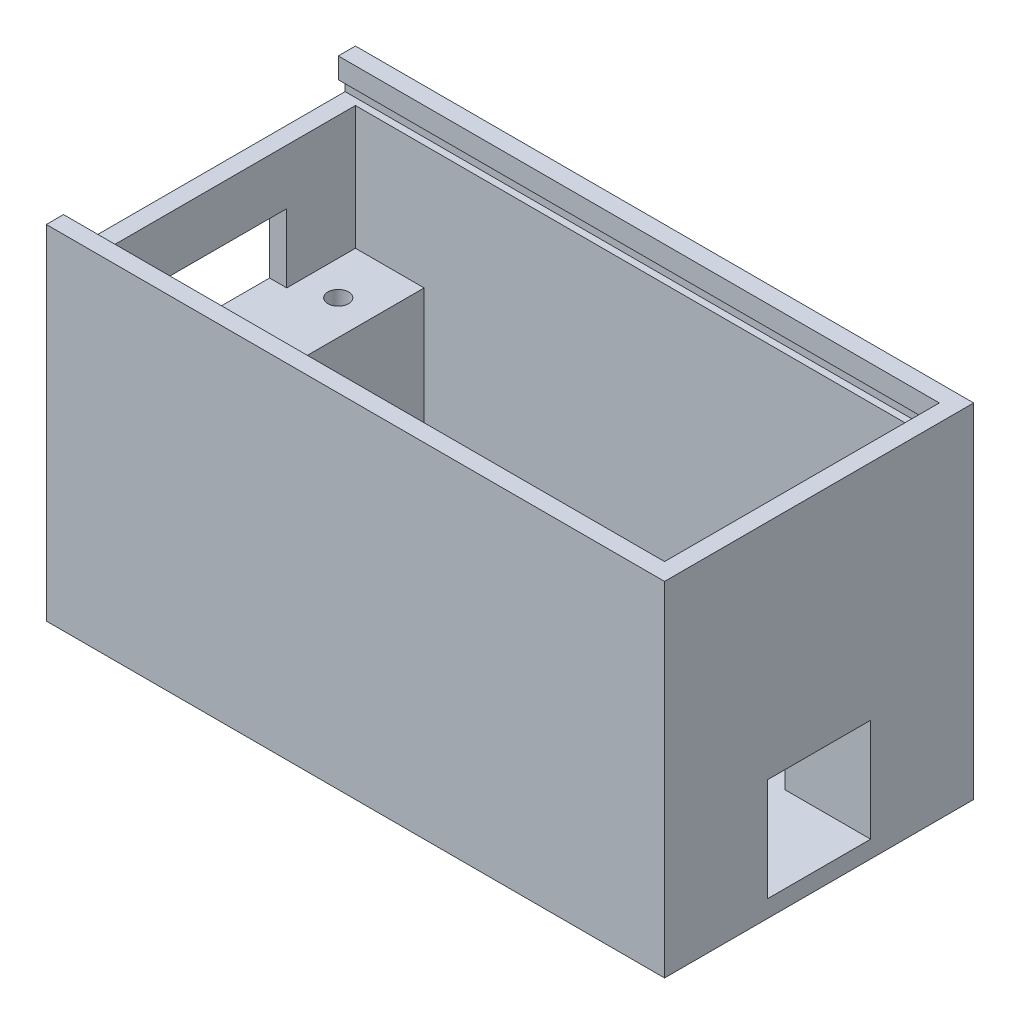
SolidWorks part; units mm, degrees
ref_plane "Front Plane" through (0, 0, 0) normal (0, 0, 1) x (1, 0, 0)
ref_plane "Top Plane" through (0, 0, 0) normal (0, 1, 0) x (1, 0, 0)
ref_plane "Right Plane" through (0, 0, 0) normal (1, 0, 0) x (0, 0, -1)
sketch "Sketch1" plane through (0, 0, 0) normal (0, 1, 0) x (1, 0, 0)
  line L1 (-40.1376, 25.9551) -> (49.8624, 25.9551)
  line L2 (-40.1376, 25.9551) -> (-40.1376, -19.0449)
  line L3 (-40.1376, -19.0449) -> (49.8624, -19.0449)
  line L4 (49.8624, 25.9551) -> (49.8624, -19.0449)
extrude "Boss-Extrude1" add sketch "Sketch1" along normal blind 50
shell "Shell1" thickness 2.5
sketch "Sketch2" plane through (-37.6376, 0, 0) normal (1, 0, 0) x (0, 0, -1)
  line L0 (-16.5449, 50) -> (-16.5449, 2.5) construction
  line L1 (23.4551, 2.5) -> (-16.5449, 2.5)
  line L2 (23.4551, 2.5) -> (23.4551, 27)
  line L3 (23.4551, 27) -> (-16.5449, 27)
  line L4 (-16.5449, 2.5) -> (-16.5449, 27)
extrude "Boss-Extrude2" add sketch "Sketch2" along normal blind 10
sketch "Sketch3" plane through (47.3624, 0, 0) normal (-1, 0, 0) x (0, 0, 1)
  line L0 (16.5449, 50) -> (16.5449, 2.5) construction
  line L5 (-23.4551, 2.5) -> (16.5449, 2.5)
  line L6 (-23.4551, 2.5) -> (-23.4551, 22)
  line L7 (-23.4551, 22) -> (16.5449, 22)
  line L8 (16.5449, 2.5) -> (16.5449, 22)
extrude "Boss-Extrude3" add sketch "Sketch3" along normal blind 10
sketch "Sketch9" plane through (-37.6376, 0, 0) normal (1, 0, 0) x (0, 0, -1)
  line L1 (23.4551, 27) -> (-16.5449, 27) construction
  line L2 (13.4551, 37) -> (-6.5449, 37)
  line L3 (13.4551, 37) -> (13.4551, 27)
  line L4 (13.4551, 27) -> (-6.5449, 27)
  line L5 (-6.5449, 37) -> (-6.5449, 27)
  line L6 (13.4551, 37) -> (-6.5449, 27) construction
  line L7 (13.4551, 27) -> (-6.5449, 37) construction
  point P3 (3.4551, 34.5)
  point P4 (3.4551, 32)
extrude "Cut-Extrude3" cut sketch "Sketch9" against normal blind 2.5
sketch "Sketch13" plane through (-37.6376, 0, 0) normal (1, 0, 0) x (0, 0, -1)
  line L0 (-16.5449, 50) -> (-16.5449, 27) construction
  line L1 (23.4551, 50) -> (-16.5449, 50)
  line L2 (23.4551, 50) -> (23.4551, 45)
  line L3 (23.4551, 45) -> (-16.5449, 45)
  line L4 (-16.5449, 50) -> (-16.5449, 45)
extrude "Cut-Extrude6" cut sketch "Sketch13" against normal blind 2.5
sketch "Sketch14" plane through (0, 0, -23.4551) normal (0, 0, 1) x (1, 0, 0)
  line L0 (47.3624, 50) -> (47.3624, 22) construction
  line L1 (-40.1376, 45) -> (47.3624, 45)
  line L2 (-40.1376, 45) -> (-40.1376, 47)
  line L3 (-40.1376, 47) -> (47.3624, 47)
  line L4 (47.3624, 45) -> (47.3624, 47)
sketch "Sketch15" plane through (0, 0, 16.5449) normal (0, 0, -1) x (-1, 0, 0)
  line L0 (-47.3624, 50) -> (-47.3624, 22) construction
  line L1 (40.1376, 45) -> (-47.3624, 45)
  line L2 (40.1376, 45) -> (40.1376, 47)
  line L3 (40.1376, 47) -> (-47.3624, 47)
  line L4 (-47.3624, 45) -> (-47.3624, 47)
extrude "Cut-Extrude7" cut sketch "Sketch14" against normal blind 1
extrude "Cut-Extrude8" cut sketch "Sketch15" against normal blind 1
sketch "Sketch16" plane through (0, 27, 0) normal (0, 1, 0) x (1, 0, 0)
  line L0 (-37.6376, -16.5449) -> (-27.6376, 23.4551)
  line L1 (-27.6376, -16.5449) -> (-37.6376, 23.4551)
  line L2 (-32.6376, -16.5449) -> (-32.6376, 23.4551)
  line L3 (-27.6376, -16.5449) -> (-37.6376, -16.5449) construction
  line L4 (-27.6376, 23.4551) -> (-37.6376, 23.4551) construction
  circle A0 centre (-32.6376, 3.4551) radius 12.5
  point P8 (-32.6376, 3.4551)
  point P17 (-32.6376, -9.0449)
  point P18 (-32.6376, 15.9551)
sketch "Sketch17" plane through (0, 27, 0) normal (0, 1, 0) x (1, 0, 0)
  circle A0 centre (-32.6376, -9.0449) radius 1.5
extrude "Cut-Extrude9" cut sketch "Sketch17" against normal blind 27
sketch "Sketch18" plane through (0, 27, 0) normal (0, 1, 0) x (1, 0, 0)
  circle A0 centre (-32.6376, 15.9551) radius 1.5
extrude "Cut-Extrude10" cut sketch "Sketch18" against normal blind 27
sketch "Sketch19" plane through (0, 22, 0) normal (0, 1, 0) x (1, 0, 0)
  line L0 (47.3624, 23.4551) -> (37.3624, -16.5449)
  line L1 (37.3624, 23.4551) -> (47.3624, -16.5449)
  line L2 (42.3624, 23.4551) -> (42.3624, -16.5449)
  line L3 (37.3624, 23.4551) -> (47.3624, 23.4551) construction
  line L4 (37.3624, -16.5449) -> (47.3624, -16.5449) construction
  circle A0 centre (42.3624, 3.4551) radius 12.5
  point P16 (42.3624, 15.9551)
  point P17 (42.3624, -9.0449)
sketch "Sketch20" plane through (0, 22, 0) normal (0, 1, 0) x (1, 0, 0)
  circle A0 centre (42.3624, 15.9551) radius 1.5
sketch "Sketch21" plane through (0, 22, 0) normal (0, 1, 0) x (1, 0, 0)
  circle A0 centre (42.3624, -9.0449) radius 1.5
extrude "Cut-Extrude11" cut sketch "Sketch20" against normal blind 22
extrude "Cut-Extrude12" cut sketch "Sketch21" against normal blind 22
sketch "Sketch22" plane through (0, 0, 0) normal (0, -1, 0) x (1, 0, 0)
  circle A0 centre (-32.6376, -15.9551) radius 3
  circle A1 centre (-32.6376, 9.0449) radius 3
  circle A2 centre (42.3624, -15.9551) radius 3
  circle A3 centre (42.3624, 9.0449) radius 3
extrude "Cut-Extrude13" cut sketch "Sketch22" against normal blind 5
sketch "Sketch25" plane through (37.3624, 0, 0) normal (-1, 0, 0) x (0, 0, 1)
  line L0 (-23.4551, 2.5) -> (16.5449, 2.5) construction
  circle A0 centre (-3.4551, 2.5) radius 7.5
  point P4 (-10.9551, 2.5)
  point P5 (4.0449, 2.5)
sketch "Sketch26" plane through (37.3624, 0, 0) normal (-1, 0, 0) x (0, 0, 1)
  line L1 (-10.9551, 2.5) -> (4.0449, 2.5)
  line L2 (-10.9551, 2.5) -> (-10.9551, 17.5)
  line L3 (-10.9551, 17.5) -> (4.0449, 17.5)
  line L4 (4.0449, 2.5) -> (4.0449, 17.5)
extrude "Cut-Extrude14" cut sketch "Sketch26" against normal blind 12.5
